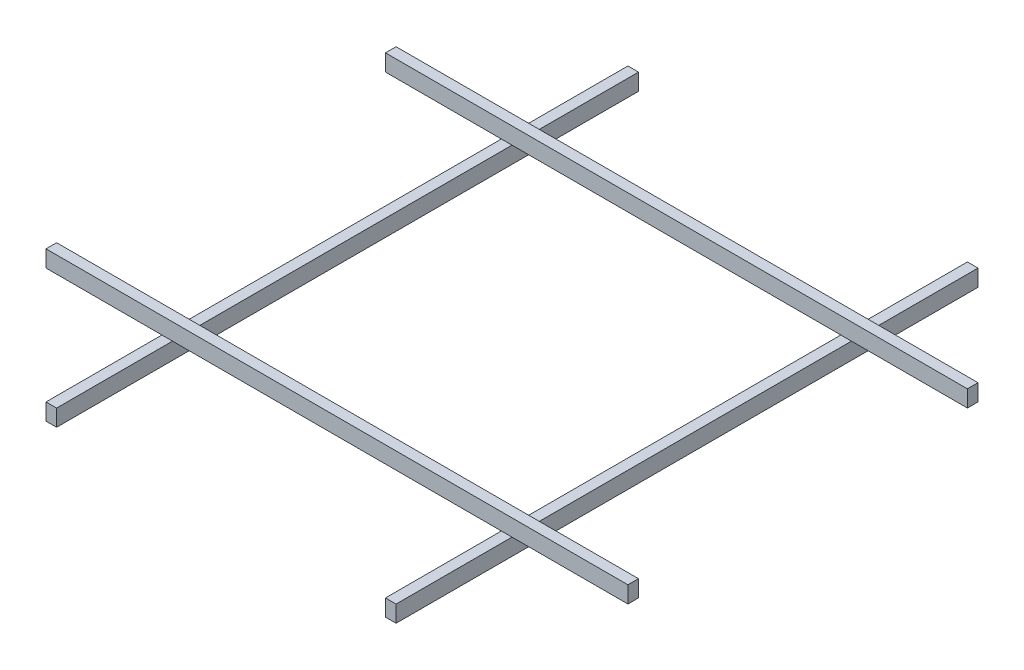
SolidWorks part; units mm, degrees
material "Doug Fir"
ref_plane "Front Plane" through (0, 0, 0) normal (0, 0, 1) x (1, 0, 0)
ref_plane "Top Plane" through (0, 0, 0) normal (0, 1, 0) x (1, 0, 0)
ref_plane "Right Plane" through (0, 0, 0) normal (1, 0, 0) x (0, 0, -1)
sketch "Lower Level" plane through (0, 0, 0) normal (0, 1, 0) x (1, 0, 0)
  line L0 (711.2, 0) -> (711.2, 4876.8)
  line L1 (3556, 0) -> (3556, 4876.8)
  line L2 (711.2, 2438.4) -> (3556, 2438.4) construction
  point P7 (2133.6, 2438.4)
  dimension "D1" = 4876.8
  dimension "D2" = 1422.4
ref_plane "Plane2" through (0, 139.7, 0) normal (0, 1, 0) x (1, 0, 0)
sketch "Sketch12" plane through (0, 139.7, 0) normal (0, 1, 0) x (1, 0, 0)
  line L0 (-304.8, 3860.8) -> (4572, 3860.8)
  line L1 (4572, 1016) -> (-304.8, 1016)
  line L2 (2133.6, 3860.8) -> (2133.6, 1016) construction
  point P0 (2133.6, 2438.4)
  point P6 (2133.6, 1016)
  point P7 (2133.6, 3860.8)
  point P10 (2133.6, 2438.4)
  dimension "D1" = 4876.8
  dimension "D2" = 1422.4
other "Profiles 4X6(1)"
ref_plane "Plane1" through (711.2, 0, 0) normal (0, 0, -1) x (-1, 0, 0)
sketch "Sketch1" plane through (711.2, 0, 0) normal (0, 0, -1) x (-1, 0, 0)
  line L1 (-44.45, 69.85) -> (44.45, 69.85)
  line L2 (-44.45, 69.85) -> (-44.45, -69.85)
  line L3 (-44.45, -69.85) -> (44.45, -69.85)
  line L4 (44.45, 69.85) -> (44.45, -69.85)
  line L5 (-44.45, 69.85) -> (44.45, -69.85) construction
  line L6 (-44.45, -69.85) -> (44.45, 69.85) construction
  point P0 (0, 0)
  point P6 (0, 69.85)
  point P7 (0, -69.85)
  point P8 (44.45, 0)
  point P9 (-44.45, 0)
  point P10 (0, 0)
  dimension "D1" = 88.9
  dimension "D2" = 139.7
sketch3d "3DSketch2"
  line L0 (2133.6, 139.7, -2438.4) -> (2133.6, 0, -2438.4)
  line L1 (711.2, 0, -2438.4) -> (3556, 0, -2438.4) construction
equation "\"Width\" = 56"
equation "\"Length\"=192"
equation "\"D1@Lower Level\"=\"Length\""
equation "\"D2@Lower Level\"=\"Width\""
equation "\"D1@Sketch12\"=\"Length\""
equation "\"D2@Sketch12\"=\"Width\""
